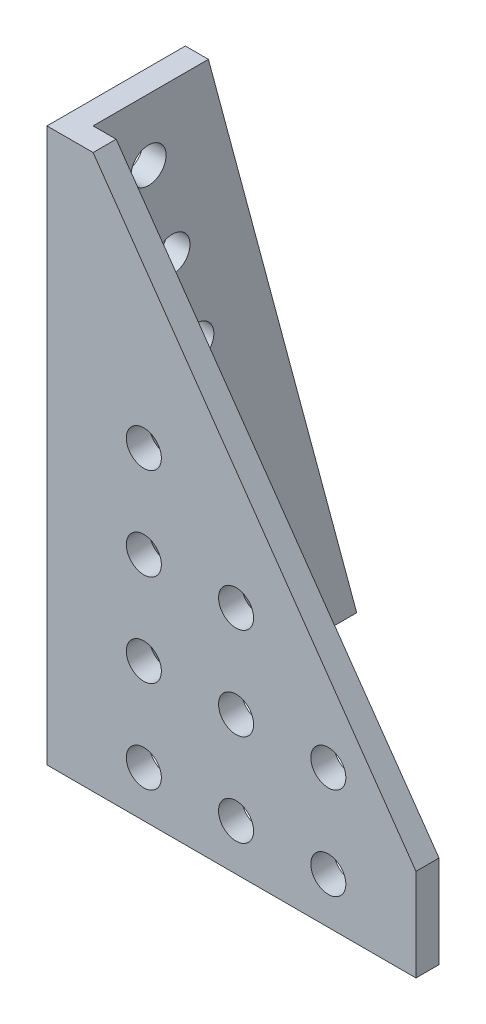
SolidWorks part; units mm, degrees
ref_plane "Front Plane" through (0, 0, 0) normal (0, 0, 1) x (1, 0, 0)
ref_plane "Top Plane" through (0, 0, 0) normal (0, 1, 0) x (1, 0, 0)
ref_plane "Right Plane" through (0, 0, 0) normal (1, 0, 0) x (0, 0, -1)
sketch "Sketch1" plane through (0, 0, 0) normal (0, 1, 0) x (1, 0, 0)
  line L0 (0, 50.8) -> (0, 0)
  line L1 (0, 50.8) -> (3.175, 50.8)
  line L2 (3.175, 50.8) -> (3.175, 3.175)
  line L3 (3.175, 3.175) -> (50.8, 3.175)
  line L4 (50.8, 3.175) -> (50.8, 0)
  line L5 (0, 0) -> (50.8, 0)
  dimension "D1" = 50.8
  dimension "D2" = 50.8
  dimension "D3" = 3.175
  dimension "D4" = 3.175
extrude "Boss-Extrude1" add sketch "Sketch1" along normal blind 76.2
sketch "Sketch2" plane through (0, 0, -3.175) normal (0, 0, -1) x (-1, 0, 0)
  line L0 (-6.35, 76.2) -> (-50.8, 12.7188)
  line L1 (-50.8, 76.2) -> (-3.175, 76.2) construction
  line L2 (-50.8, 76.2) -> (-50.8, 0) construction
  line L3 (-50.8, 12.7188) -> (-50.8, 76.2)
  line L4 (-50.8, 76.2) -> (-6.35, 76.2)
  line L5 (-13.335, 6.35) -> (-13.335, 40.0523) construction
  line L6 (-26.035, 6.35) -> (-26.035, 41.8276) construction
  line L7 (-3.175, 76.2) -> (-3.175, 0) construction
  line L8 (-50.8, 0) -> (-3.175, 0) construction
  circle A0 centre (-13.335, 6.35) radius 2.413
  circle A1 centre (-26.035, 6.35) radius 2.413
  circle A2 centre (-13.335, 19.05) radius 2.413
  circle A3 centre (-13.335, 31.75) radius 2.413
  circle A4 centre (-13.335, 44.45) radius 2.413
  circle A5 centre (-13.335, 57.15) radius 2.413 construction
  circle A6 centre (-26.035, 19.05) radius 2.413
  circle A7 centre (-26.035, 31.75) radius 2.413
  circle A8 centre (-38.735, 19.05) radius 2.413
  circle A9 centre (-38.735, 6.35) radius 2.413
  point P27 (0, 0)
  point P31 (0, 0)
  line M5 (-3.175, 76.2) -> (-50.8, 76.2)
  line M6 (-50.8, 76.2) -> (-50.8, 0)
  dimension "D7" = 4.826
  dimension "D8" = 4.826
  dimension "D1" = 55
  dimension "D2" = 44.45
  dimension "D3" = 10.16
  dimension "D4" = 22.86
  dimension "D5" = 6.35
  dimension "D6" = 6.35
  dimension "D9" = 5
  dimension "D10" = 3
  dimension "D11" = 2
extrude "Cut-Extrude1" cut sketch "Sketch2" against normal blind 3.175 contours L0 M5 M6 | A5 | A4 | A3 | A2 | A0 | A1 | A6 | A7 | A8 | A9
sketch "Sketch4" plane through (3.175, 0, 0) normal (1, 0, 0) x (0, 0, -1)
  line L0 (19.05, 76.2) -> (50.8, 76.2)
  line L1 (3.175, 76.2) -> (50.8, 76.2) construction
  line L2 (50.8, 76.2) -> (50.8, -42.2926)
  line L3 (50.8, -42.2926) -> (19.05, 76.2)
  line L4 (16.58, 46.1629) -> (27.2478, 6.35) construction
  line L5 (3.175, 0) -> (50.8, 0) construction
  circle A0 centre (27.2478, 6.35) radius 2.413
  circle A1 centre (23.9608, 18.6173) radius 2.413
  circle A2 centre (20.6738, 30.8845) radius 2.413
  circle A3 centre (17.3868, 43.1518) radius 2.413
  circle A4 centre (14.0998, 55.419) radius 2.413
  circle A5 centre (10.8128, 67.6863) radius 2.413
  dimension "D5" = 4.826
  dimension "D4" = 6.35
  dimension "D1" = 31.75
  dimension "D2" = 75
  dimension "D3" = 10.16
  dimension "D6" = 6
extrude "Cut-Extrude2" cut sketch "Sketch4" against normal through all
